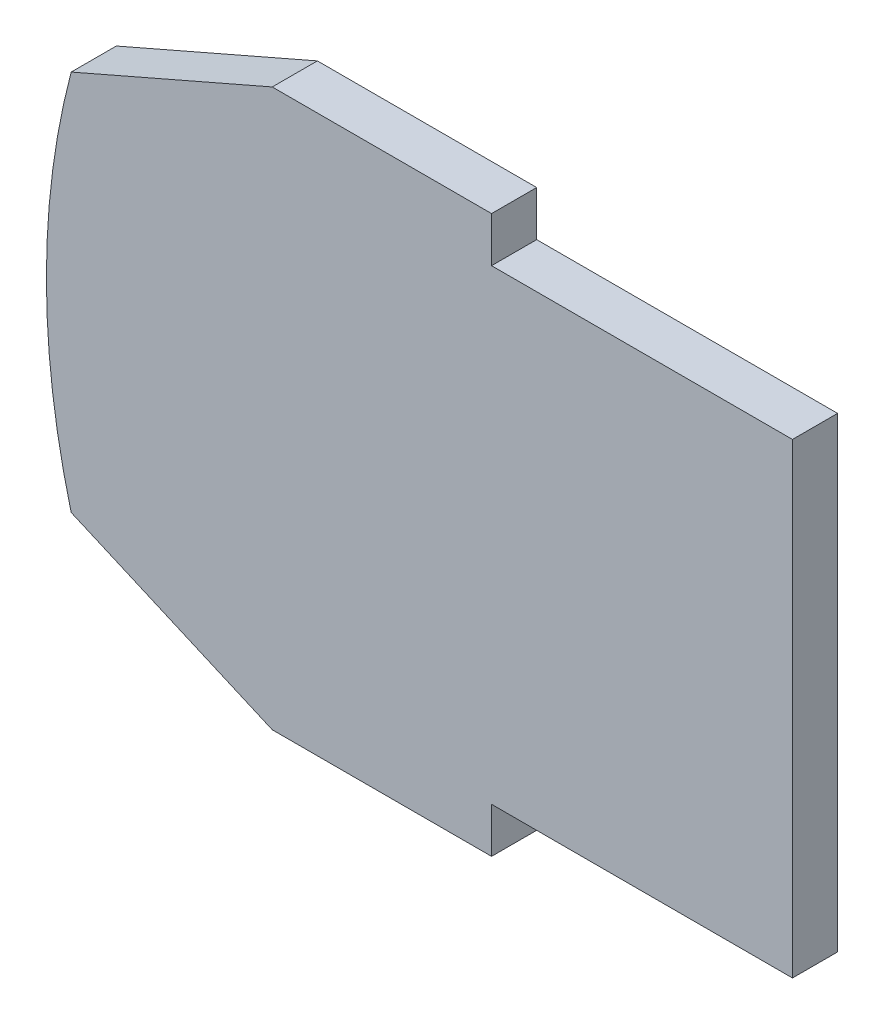
SolidWorks part; units mm, degrees
ref_plane "Front" through (0, 0, 0) normal (0, 0, 1) x (1, 0, 0)
ref_plane "Top" through (0, 0, 0) normal (0, 1, 0) x (1, 0, 0)
ref_plane "Right" through (0, 0, 0) normal (1, 0, 0) x (0, 0, -1)
sketch "Sketch1" plane through (0, 0, 0) normal (0, 0, 1) x (1, 0, 0)
  line L0 (570.054, -52.2279) -> (555.4774, -52.2279)
  line L1 (570.054, -89.2279) -> (555.4774, -89.2279)
  line L2 (555.4774, -89.2279) -> (542.115, -83.4036)
  line L3 (555.4774, -52.2279) -> (542.1149, -58.052)
  line L4 (570.054, -86.2279) -> (570.054, -89.2279)
  line L5 (590.054, -70.7276) -> (590.054, -55.2279)
  line L6 (590.054, -70.7276) -> (590.054, -86.2279)
  line L7 (590.054, -86.2279) -> (570.054, -86.2279)
  line L8 (590.054, -55.2279) -> (570.054, -55.2279)
  line L9 (570.054, -55.2279) -> (570.054, -52.2279)
  arc A0 (542.1149, -58.052) -> (542.115, -83.4036) centre (590.054, -70.7276) ccw
  dimension "D1" = 3
  dimension "D2" = 3
  dimension "D3" = 31
  dimension "D4" = 20
extrude "Base-Extrude" add sketch "Sketch1" along normal blind 3
